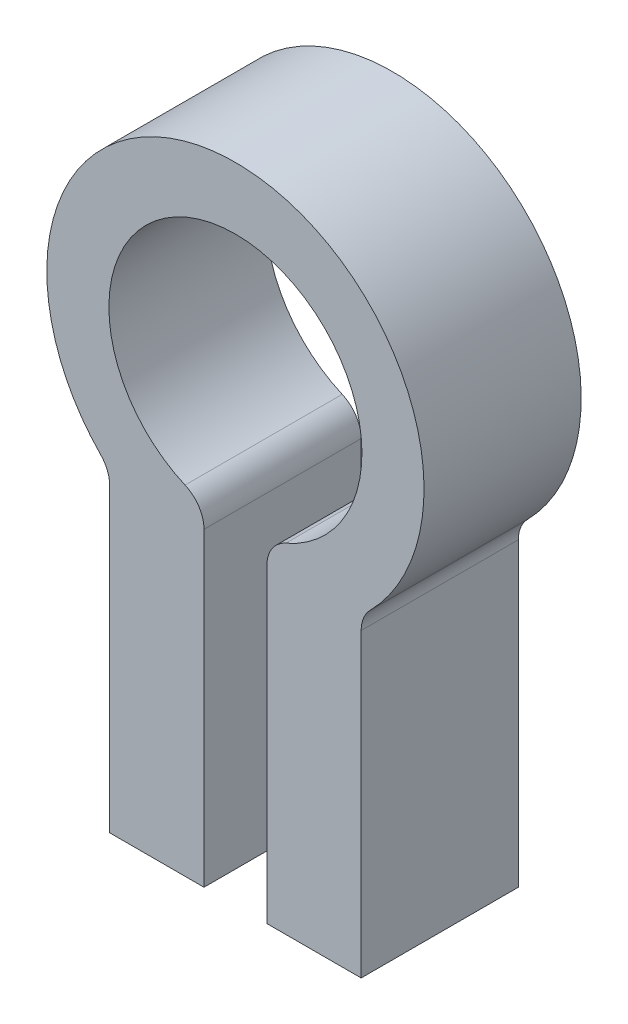
SolidWorks part; units mm, degrees
ref_plane "Front Plane" through (0, 0, 0) normal (0, 0, 1) x (1, 0, 0)
ref_plane "Top Plane" through (0, 0, 0) normal (0, 1, 0) x (1, 0, 0)
ref_plane "Right Plane" through (0, 0, 0) normal (1, 0, 0) x (0, 0, -1)
sketch "Sketch1" plane through (0, 0, 0) normal (0, 0, 1) x (1, 0, 0)
  line L0 (0, 0) -> (0, -8.1505) construction
  line L1 (-1, -3.8988) -> (-1, -14.4721)
  line L2 (-1, -14.4721) -> (-4, -14.4721)
  line L3 (-4, -14.4721) -> (-4, -4.4721)
  line L4 (1, -3.8988) -> (1, -14.4721)
  line L5 (1, -14.4721) -> (4, -14.4721)
  line L6 (4, -14.4721) -> (4, -4.4721)
  circle A0 centre (0, 0) radius 4.025 construction
  arc A1 (1, -3.8988) -> (-1, -3.8988) centre (0, 0) ccw
  arc A2 (4, -4.4721) -> (-4, -4.4721) centre (0, 0) ccw
  point P5 (-2.8696, -5.5556)
  point P13 (0, 0)
  point P14 (-4.5778, -5.157)
  dimension "D1" = 8.05
  dimension "D3" = 6
  dimension "D2" = 10
  dimension "D4" = 8
  dimension "D5" = 2
extrude "Boss-Extrude1" add sketch "Sketch1" along normal blind 5
fillet "Fillet1" radius 1 4 edges at (1, -3.8988, 2.5) (-1, -3.8988, 2.5) (-4, -4.4721, 2.5) (4, -4.4721, 2.5)
